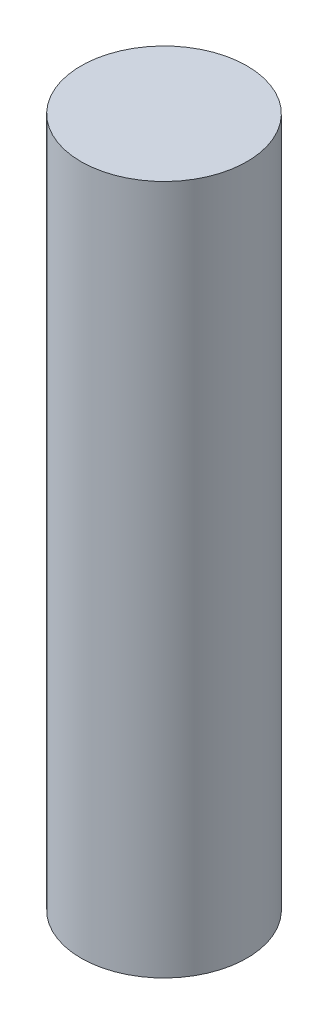
SolidWorks part; units mm, degrees
ref_plane "Front Plane" through (0, 0, 0) normal (0, 0, 1) x (1, 0, 0)
ref_plane "Top Plane" through (0, 0, 0) normal (0, 1, 0) x (1, 0, 0)
ref_plane "Right Plane" through (0, 0, 0) normal (1, 0, 0) x (0, 0, -1)
sketch "Sketch2" plane through (0, 0, 0) normal (0, 1, 0) x (1, 0, 0)
  circle A0 centre (0, 0) radius 3.85
  dimension "D1" = 7.7
extrude "Boss-Extrude1" add sketch "Sketch2" along normal mid plane 32
